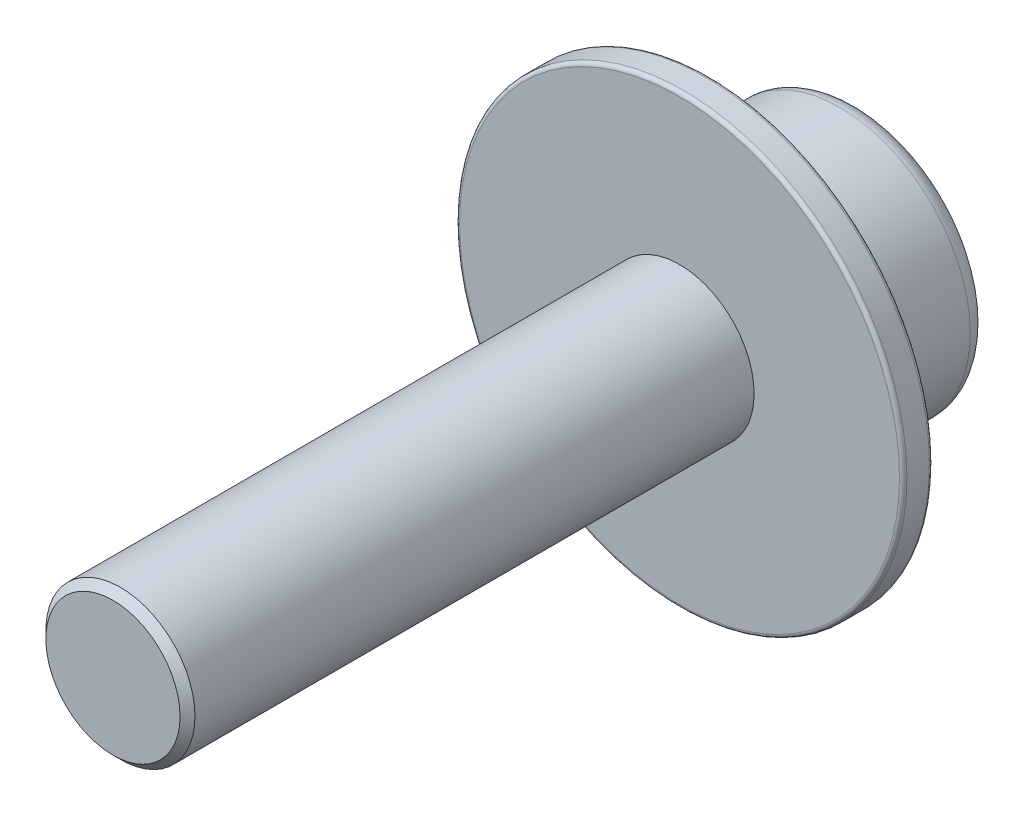
SolidWorks part; units mm, degrees
material "AISI 4340 Steel, annealed"
ref_plane "Front Plane" through (0, 0, 0) normal (0, 0, 1) x (1, 0, 0)
ref_plane "Top Plane" through (0, 0, 0) normal (0, 1, 0) x (1, 0, 0)
ref_plane "Right Plane" through (0, 0, 0) normal (1, 0, 0) x (0, 0, -1)
sketch "Sketch1" plane through (0, 0, 0) normal (0, 0, 1) x (1, 0, 0)
  circle A0 centre (0, 0) radius 3.5
  dimension "D1" = 7
extrude "Boss-Extrude1" add sketch "Sketch1" along normal blind 4
sketch "Sketch2" plane through (0, 0, 4) normal (0, 0, 1) x (1, 0, 0)
  circle A0 centre (0, 0) radius 2
  dimension "D1" = 4
extrude "Boss-Extrude2" add sketch "Sketch2" along normal blind 16
sketch "Sketch3" plane through (0, 0, 0) normal (0, 0, -1) x (-1, 0, 0)
  line L1 (2.0207, 0) -> (1.0104, 1.75)
  line L2 (1.0104, 1.75) -> (-1.0104, 1.75)
  line L3 (-1.0104, 1.75) -> (-2.0207, 0)
  line L4 (-2.0207, 0) -> (-1.0104, -1.75)
  line L5 (-1.0104, -1.75) -> (1.0104, -1.75)
  line L6 (1.0104, -1.75) -> (2.0207, 0)
  circle A0 centre (0, 0) radius 1.75 construction
  dimension "D1" = 3.5
extrude "Cut-Extrude1" cut sketch "Sketch3" against normal blind 2.5
fillet "Fillet1" radius 0.5 9 edges at (3.5, 0, 4) (2, 0, 4) (3.5, 0, 0) (0, 1.75, 0) (1.5155, 0.875, 0) (1.5155, -0.875, 0) (0, -1.75, 0) (-1.5155, -0.875, 0) (-1.5155, 0.875, 0)
chamfer "Chamfer1" distance 0.2 angle 45 1 edges at (2, 0, 20)
sketch "Sketch4" plane through (0, 0, 4) normal (0, 0, 1) x (1, 0, 0)
  circle A0 centre (0, 0) radius 6
  dimension "D1" = 12
extrude "Boss-Extrude3" add sketch "Sketch4" along normal blind 0.8
fillet "Fillet2" radius 0.1 2 edges at (6, 0, 4.8) (6, 0, 4)
